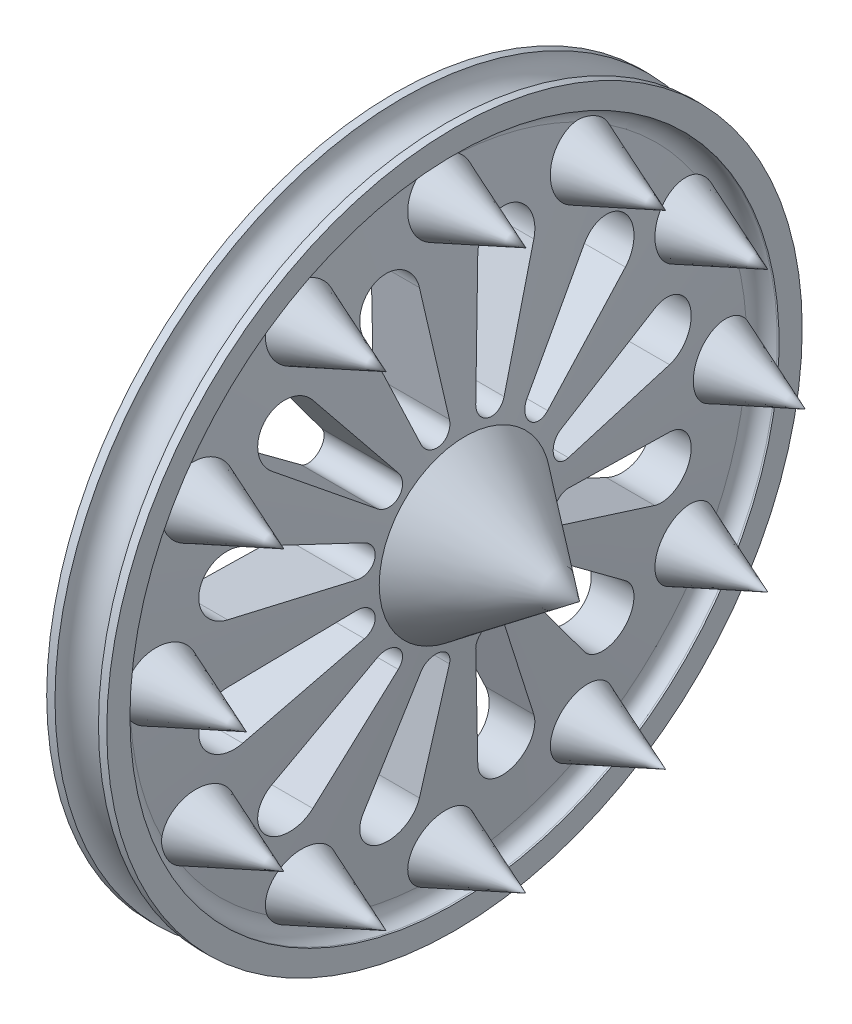
SolidWorks part; units mm, degrees
ref_plane "Front Plane" through (0, 0, 0) normal (0, 0, 1) x (1, 0, 0)
ref_plane "Top Plane" through (0, 0, 0) normal (0, 1, 0) x (1, 0, 0)
ref_plane "Right Plane" through (0, 0, 0) normal (1, 0, 0) x (0, 0, -1)
sketch "Sketch3" plane through (0, 0, 0) normal (0, 1, 0) x (1, 0, 0)
  line L0 (0, 7.62) -> (0, 28.5726) construction
  line L1 (-3.5611, 0) -> (3.5611, 0)
  line L2 (1.2165, 27.0266) -> (3.5611, 7.5247)
  line L3 (-3.5611, 7.5247) -> (-3.5611, 0)
  line L4 (3.5611, 7.5247) -> (13.596, 0)
  line L5 (-2.6328, 28.4482) -> (-2.4774, 28.4482)
  line L6 (2.6328, 30.48) -> (1.905, 30.48)
  line L7 (2.6328, 30.48) -> (2.6328, 28.4482)
  line L8 (2.6328, 28.4482) -> (2.4774, 28.4482)
  line L9 (-2.6328, 30.48) -> (-2.6328, 28.4482)
  line L10 (-2.6328, 30.48) -> (-1.905, 30.48)
  line L11 (13.596, 0) -> (3.5611, 0)
  line L13 (-1.2165, 27.0266) -> (-3.5611, 7.5247)
  line L14 (13.596, 0) -> (21.3367, 0) construction
  arc A0 (-1.905, 30.48) -> (1.905, 30.48) centre (0, 30.48) ccw
  arc A1 (-2.4774, 28.4482) -> (-1.2165, 27.0266) centre (-2.4774, 27.1782) cw
  arc A2 (1.2165, 27.0266) -> (2.4774, 28.4482) centre (2.4774, 27.1782) cw
  point P12 (1.905, 30.48)
  point P20 (0, 0)
  point P22 (-1.0456, 28.4482)
  point P26 (1.0456, 28.4482)
  dimension "D1" = 3.81
  dimension "D3" = 1.27
  dimension "D2" = 30.48
  dimension "D4" = 30.48
  dimension "D5" = 21.0741
  dimension "D6" = 7.7407
  dimension "D7" = 7.5247
  dimension "D8" = 7.5247
  dimension "D10" = 10.0348
revolve "Revolve1" add sketch "Sketch3" angle 360 about L14
sketch "Sketch4" plane through (0, 0, 0) normal (0, 1, 0) x (1, 0, 0)
  line L0 (0, 28.014) -> (8.89, 24.4936)
  line L1 (8.89, 24.4936) -> (0, 24.4936) construction
  line L2 (0, 28.014) -> (0, 24.4936)
  line L3 (0, 24.4936) -> (8.89, 24.4936)
  line L4 (0, 30.9559) -> (0, 21.1106) construction
  dimension "D2" = 8.89
  dimension "D4" = 8.89
  dimension "D5" = 9.8453
revolve "Revolve2" add sketch "Sketch4" angle 360 about L1
sketch "Sketch5" plane through (0, 0, 0) normal (0, 1, 0) x (1, 0, 0)
  line L0 (0, 0) -> (36.4977, 0) construction
  dimension "D1" = 36.4977
pattern_circular "CirPattern1" count 12 over 360 about axis through (0, 0, 0) along (1, 0, 0) of "Revolve2"
sketch "Sketch6" plane through (0, 0, 0) normal (1, 0, 0) x (0, 0, -1)
  line L0 (0, 34.6684) -> (0, -10.3561) construction
  line L1 (-4.8409, 0) -> (-1.3123, -10.3561)
  line L2 (-1.3123, -10.3561) -> (1.3123, -10.3561)
  line L3 (-0.0353, 0.1403) -> (-0.8308, -0.8208)
  line L4 (-0.8039, -1.1069) -> (-0.732, -1.1664)
  line L5 (-0.4083, -1.0697) -> (-0.0353, 0.1403)
  line L6 (-0.0353, 0.1403) -> (-0.068, 0.1287)
  line L7 (0.4083, -1.0697) -> (0.0353, 0.1403)
  line L8 (0.8039, -1.1069) -> (0.732, -1.1664)
  line L9 (0.0353, 0.1403) -> (0.8308, -0.8208)
  line L10 (4.8409, 0) -> (1.3123, -10.3561)
  arc A0 (6.4132, 3.483) -> (-6.4132, 3.483) centre (0, 10.1179) ccw
  arc A1 (-5.6795, 2.1114) -> (-4.8409, 0) centre (0, 3.1448) ccw
  arc A2 (-5.6795, 2.1114) -> (-6.4132, 3.483) centre (-8.1784, 1.6566) ccw
  arc A3 (-4.023, 3.0379) -> (-3.3253, 2.3796) centre (-3.2677, 3.1394) ccw
  arc A4 (-0.8308, -0.8208) -> (-0.8039, -1.1069) centre (-0.6743, -0.9504) ccw
  arc A5 (-0.732, -1.1664) -> (-0.4083, -1.0697) centre (-0.6025, -1.0099) ccw
  arc A6 (0.732, -1.1664) -> (0.4083, -1.0697) centre (0.6025, -1.0099) cw
  arc A7 (0.8308, -0.8208) -> (0.8039, -1.1069) centre (0.6743, -0.9504) cw
  arc A8 (4.023, 3.0379) -> (3.3253, 2.3796) centre (3.2677, 3.1394) cw
  arc A9 (5.6795, 2.1114) -> (6.4132, 3.483) centre (8.1784, 1.6566) cw
  arc A10 (5.6795, 2.1114) -> (4.8409, 0) centre (0, 3.1448) cw
  ellipse E0 centre (-0.9604, -13.2244) end of major axis (-0.9604, -18.7148) minor radius 0.2284 (-0.7657, -10.3561) -> (-1.1552, -10.3561) ccw
  ellipse E1 centre (-0.4524, -13.2244) end of major axis (-0.4524, -18.7148) minor radius 0.2284 (-0.2577, -10.3561) -> (-0.6472, -10.3561) ccw
  ellipse E2 centre (0.0556, -13.2244) end of major axis (0.0556, -18.7148) minor radius 0.2284 (0.2503, -10.3561) -> (-0.1392, -10.3561) ccw
  ellipse E3 centre (0.5636, -13.2244) end of major axis (0.5636, -18.7148) minor radius 0.2284 (0.7583, -10.3561) -> (0.3688, -10.3561) ccw
  ellipse E4 centre (1.0716, -13.2244) end of major axis (1.0716, -18.7148) minor radius 0.2284 (1.2663, -10.3561) -> (0.8768, -10.3561) ccw
  spline S0 degree 3 poles (-4.023, 3.0379) (-4.4228, 6.0131) (-3.1972, 6.0097) (-0.9016, 2.196) knots 0.060273 0.060273 0.060273 0.060273 1 1 1 1
  spline S1 degree 3 poles (-0.9016, 2.196) (-1.7095, 2.2572) (-2.5174, 2.3184) (-3.3253, 2.3796) knots 0 0 0 0 0.800788 0.800788 0.800788 0.800788
  spline S2 degree 3 poles (0.9016, 2.196) (1.7095, 2.2572) (2.5174, 2.3184) (3.3253, 2.3796) knots 0 0 0 0 0.800788 0.800788 0.800788 0.800788
  spline S3 degree 3 poles (4.023, 3.0379) (4.4228, 6.0131) (3.1972, 6.0097) (0.9016, 2.196) knots 0.060273 0.060273 0.060273 0.060273 1 1 1 1
  point P19 (0.4978, -1.3602)
  point P24 (-0.9604, -0.9773)
  point P27 (-0.4978, -1.3602)
  point P45 (0, -10.3561)
  point P46 (0.9604, -0.9773)
  dimension "D2" = 2.54
  dimension "D3" = 0.762
  dimension "D10" = 0.2032
  dimension "D4" = 10.9408
  dimension "D5" = 1.3123
  dimension "D6" = 1.4509
  dimension "D7" = 0.6005
  dimension "D8" = 1.5702
  dimension "D9" = 0.0348
sketch "Sketch7" plane through (-3.5611, 0, 0) normal (-1, 0, 0) x (0, 0, 1)
  line L1 (0, 6.9951) -> (-6.0579, 3.4975)
  line L2 (-6.0579, 3.4975) -> (-6.0579, -3.4975)
  line L3 (-6.0579, -3.4975) -> (0, -6.9951)
  line L4 (0, -6.9951) -> (6.0579, -3.4975)
  line L5 (6.0579, -3.4975) -> (6.0579, 3.4975)
  line L6 (6.0579, 3.4975) -> (0, 6.9951)
  circle A0 centre (0, 0) radius 6.0579 construction
  dimension "D1" = 12.1158
extrude "Cut-Extrude1" cut sketch "Sketch7" against normal blind 5.08
sketch "Sketch8" plane through (0, 0, 0) normal (1, 0, 0) x (0, 0, -1)
  line L0 (0, 0) -> (26.5839, 26.5839) construction
  line L1 (27.0266, 0) -> (7.5247, 0) construction
  line L2 (7.4576, 5.6376) -> (15.4951, 11.8985)
  line L3 (5.6376, 7.4576) -> (11.8985, 15.4951)
  line L4 (8.6111, 3.6397) -> (18.0519, 7.4699)
  line L5 (9.2772, 1.1535) -> (19.3684, 2.5568)
  line L6 (9.2772, -1.1535) -> (19.3684, -2.5568)
  line L7 (8.6111, -3.6397) -> (18.0519, -7.4699)
  line L8 (7.4576, -5.6376) -> (15.4951, -11.8985)
  line L9 (5.6376, -7.4576) -> (11.8985, -15.4951)
  line L10 (3.6397, -8.6111) -> (7.4699, -18.0519)
  line L11 (1.1535, -9.2772) -> (2.5568, -19.3684)
  line L12 (-1.1535, -9.2772) -> (-2.5568, -19.3684)
  line L13 (-3.6397, -8.6111) -> (-7.4699, -18.0519)
  line L14 (-5.6376, -7.4576) -> (-11.8985, -15.4951)
  line L15 (-7.4576, -5.6376) -> (-15.4951, -11.8985)
  line L16 (-8.6111, -3.6397) -> (-18.0519, -7.4699)
  line L17 (-9.2772, -1.1535) -> (-19.3684, -2.5568)
  line L18 (-9.2772, 1.1535) -> (-19.3684, 2.5568)
  line L19 (-8.6111, 3.6397) -> (-18.0519, 7.4699)
  line L20 (-7.4576, 5.6376) -> (-15.4951, 11.8985)
  line L21 (-5.6376, 7.4576) -> (-11.8985, 15.4951)
  line L22 (-3.6397, 8.6111) -> (-7.4699, 18.0519)
  line L23 (-1.1535, 9.2772) -> (-2.5568, 19.3684)
  line L24 (1.1535, 9.2772) -> (2.5568, 19.3684)
  line L25 (3.6397, 8.6111) -> (7.4699, 18.0519)
  arc A0 (15.4951, 11.8985) -> (11.8985, 15.4951) centre (13.9202, 13.9202) ccw
  arc A1 (5.6376, 7.4576) -> (7.4576, 5.6376) centre (6.6606, 6.6606) ccw
  arc A2 (19.3684, 2.5568) -> (18.0519, 7.4699) centre (19.0154, 5.0951) ccw
  arc A3 (8.6111, 3.6397) -> (9.2772, 1.1535) centre (9.0986, 2.438) ccw
  arc A4 (18.0519, -7.4699) -> (19.3684, -2.5568) centre (19.0154, -5.0951) ccw
  arc A5 (9.2772, -1.1535) -> (8.6111, -3.6397) centre (9.0986, -2.438) ccw
  arc A6 (11.8985, -15.4951) -> (15.4951, -11.8985) centre (13.9202, -13.9202) ccw
  arc A7 (7.4576, -5.6376) -> (5.6376, -7.4576) centre (6.6606, -6.6606) ccw
  arc A8 (2.5568, -19.3684) -> (7.4699, -18.0519) centre (5.0951, -19.0154) ccw
  arc A9 (3.6397, -8.6111) -> (1.1535, -9.2772) centre (2.438, -9.0986) ccw
  arc A10 (-7.4699, -18.0519) -> (-2.5568, -19.3684) centre (-5.0951, -19.0154) ccw
  arc A11 (-1.1535, -9.2772) -> (-3.6397, -8.6111) centre (-2.438, -9.0986) ccw
  arc A12 (-15.4951, -11.8985) -> (-11.8985, -15.4951) centre (-13.9202, -13.9202) ccw
  arc A13 (-5.6376, -7.4576) -> (-7.4576, -5.6376) centre (-6.6606, -6.6606) ccw
  arc A14 (-19.3684, -2.5568) -> (-18.0519, -7.4699) centre (-19.0154, -5.0951) ccw
  arc A15 (-8.6111, -3.6397) -> (-9.2772, -1.1535) centre (-9.0986, -2.438) ccw
  arc A16 (-18.0519, 7.4699) -> (-19.3684, 2.5568) centre (-19.0154, 5.0951) ccw
  arc A17 (-9.2772, 1.1535) -> (-8.6111, 3.6397) centre (-9.0986, 2.438) ccw
  arc A18 (-11.8985, 15.4951) -> (-15.4951, 11.8985) centre (-13.9202, 13.9202) ccw
  arc A19 (-7.4576, 5.6376) -> (-5.6376, 7.4576) centre (-6.6606, 6.6606) ccw
  arc A20 (-2.5568, 19.3684) -> (-7.4699, 18.0519) centre (-5.0951, 19.0154) ccw
  arc A21 (-3.6397, 8.6111) -> (-1.1535, 9.2772) centre (-2.438, 9.0986) ccw
  arc A22 (7.4699, 18.0519) -> (2.5568, 19.3684) centre (5.0951, 19.0154) ccw
  arc A23 (1.1535, 9.2772) -> (3.6397, 8.6111) centre (2.438, 9.0986) ccw
  point P80 (0, 0)
  dimension "D3" = 10.1882
  dimension "D1" = 37.5953
  dimension "D2" = 45
  dimension "D4" = 10.1882
  dimension "D5" = 12
extrude "Cut-Extrude2" cut sketch "Sketch8" against normal mid plane 15.24
